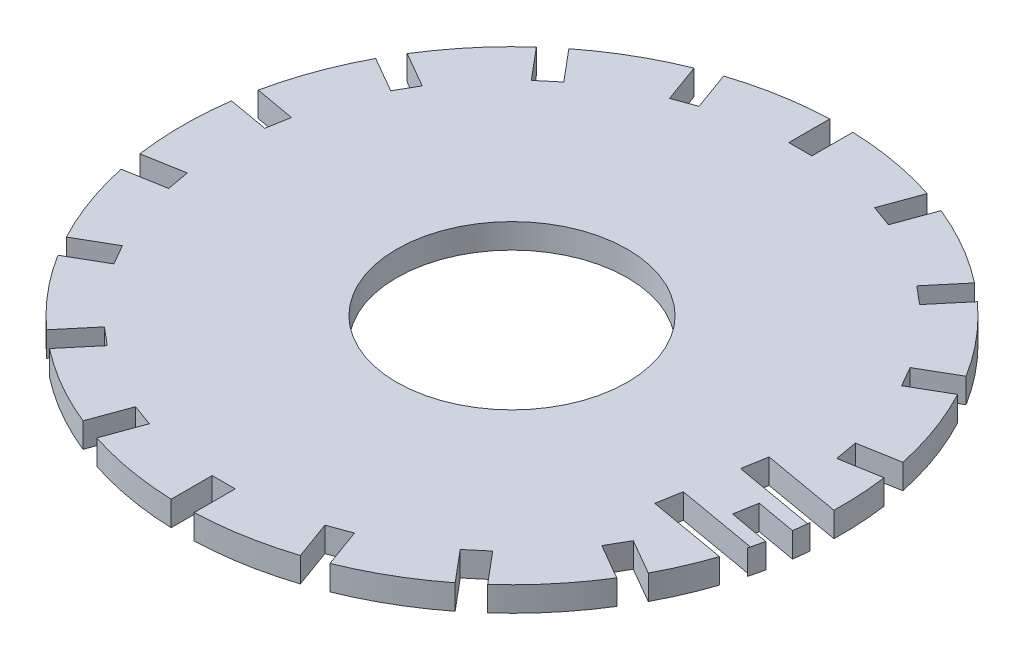
SolidWorks part; units mm, degrees
ref_plane "Plan de face" through (0, 0, 0) normal (0, 0, 1) x (1, 0, 0)
ref_plane "Plan de dessus" through (0, 0, 0) normal (0, 1, 0) x (1, 0, 0)
ref_plane "Plan de droite" through (0, 0, 0) normal (1, 0, 0) x (0, 0, -1)
sketch "Esquisse1" plane through (0, 0, 0) normal (0, 1, 0) x (1, 0, 0)
  line L0 (0, 0) -> (0, 40) construction
  line L1 (0, 40) -> (8.5644, 40) construction
  circle A0 centre (0, 0) radius 40
  circle A1 centre (0, 0) radius 14
  dimension "D1" = 80
  dimension "D2" = 28
extrude "Boss.-Extru.1" add sketch "Esquisse1" along normal blind 3
sketch "Esquisse2" plane through (0, 3, 0) normal (0, 1, 0) x (1, 0, 0)
  line L0 (0, 0) -> (0, 40) construction
  line L1 (0, 40) -> (2.8, 40) construction
  line L2 (14.9964, 37.1089) -> (13.2863, 32.4104)
  line L3 (1.4, 40) -> (-1.4, 40)
  line L4 (1.4, 40) -> (1.4, 35)
  line L5 (1.4, 35) -> (-1.4, 35)
  line L6 (-1.4, 40) -> (-1.4, 35)
  line L7 (14.9964, 37.1089) -> (12.3652, 38.0665)
  line L8 (12.3652, 38.0665) -> (10.6551, 33.3681)
  line L9 (13.2863, 32.4104) -> (10.6551, 33.3681)
  line L10 (26.784, 29.7419) -> (23.57, 25.9117)
  line L11 (26.784, 29.7419) -> (24.639, 31.5417)
  line L12 (24.639, 31.5417) -> (21.4251, 27.7115)
  line L13 (23.57, 25.9117) -> (21.4251, 27.7115)
  line L14 (35.341, 18.7876) -> (31.0109, 16.2876)
  line L15 (35.341, 18.7876) -> (33.941, 21.2124)
  line L16 (33.941, 21.2124) -> (29.6109, 18.7124)
  line L17 (31.0109, 16.2876) -> (29.6109, 18.7124)
  line L18 (39.6354, 5.5672) -> (34.7114, 4.699)
  line L19 (39.6354, 5.5672) -> (39.1492, 8.3247)
  line L20 (39.1492, 8.3247) -> (34.2252, 7.4564)
  line L21 (34.7114, 4.699) -> (34.2252, 7.4564)
  line L22 (39.1492, -8.3247) -> (34.2252, -7.4564)
  line L23 (39.1492, -8.3247) -> (39.6354, -5.5672)
  line L24 (39.6354, -5.5672) -> (34.7114, -4.699)
  line L25 (34.2252, -7.4564) -> (34.7114, -4.699)
  line L26 (33.941, -21.2124) -> (29.6109, -18.7124)
  line L27 (33.941, -21.2124) -> (35.341, -18.7876)
  line L28 (35.341, -18.7876) -> (31.0109, -16.2876)
  line L29 (29.6109, -18.7124) -> (31.0109, -16.2876)
  line L30 (24.639, -31.5417) -> (21.4251, -27.7115)
  line L31 (24.639, -31.5417) -> (26.784, -29.7419)
  line L32 (26.784, -29.7419) -> (23.57, -25.9117)
  line L33 (21.4251, -27.7115) -> (23.57, -25.9117)
  line L34 (12.3652, -38.0665) -> (10.6551, -33.3681)
  line L35 (12.3652, -38.0665) -> (14.9964, -37.1089)
  line L36 (14.9964, -37.1089) -> (13.2863, -32.4104)
  line L37 (10.6551, -33.3681) -> (13.2863, -32.4104)
  line L38 (-1.4, -40) -> (-1.4, -35)
  line L39 (-1.4, -40) -> (1.4, -40)
  line L40 (1.4, -40) -> (1.4, -35)
  line L41 (-1.4, -35) -> (1.4, -35)
  line L42 (-14.9964, -37.1089) -> (-13.2863, -32.4104)
  line L43 (-14.9964, -37.1089) -> (-12.3652, -38.0665)
  line L44 (-12.3652, -38.0665) -> (-10.6551, -33.3681)
  line L45 (-13.2863, -32.4104) -> (-10.6551, -33.3681)
  line L46 (-26.784, -29.7419) -> (-23.57, -25.9117)
  line L47 (-26.784, -29.7419) -> (-24.639, -31.5417)
  line L48 (-24.639, -31.5417) -> (-21.4251, -27.7115)
  line L49 (-23.57, -25.9117) -> (-21.4251, -27.7115)
  line L50 (-35.341, -18.7876) -> (-31.0109, -16.2876)
  line L51 (-35.341, -18.7876) -> (-33.941, -21.2124)
  line L52 (-33.941, -21.2124) -> (-29.6109, -18.7124)
  line L53 (-31.0109, -16.2876) -> (-29.6109, -18.7124)
  line L54 (-39.6354, -5.5672) -> (-34.7114, -4.699)
  line L55 (-39.6354, -5.5672) -> (-39.1492, -8.3247)
  line L56 (-39.1492, -8.3247) -> (-34.2252, -7.4564)
  line L57 (-34.7114, -4.699) -> (-34.2252, -7.4564)
  line L58 (-39.1492, 8.3247) -> (-34.2252, 7.4564)
  line L59 (-39.1492, 8.3247) -> (-39.6354, 5.5672)
  line L60 (-39.6354, 5.5672) -> (-34.7114, 4.699)
  line L61 (-34.2252, 7.4564) -> (-34.7114, 4.699)
  line L62 (-33.941, 21.2124) -> (-29.6109, 18.7124)
  line L63 (-33.941, 21.2124) -> (-35.341, 18.7876)
  line L64 (-35.341, 18.7876) -> (-31.0109, 16.2876)
  line L65 (-29.6109, 18.7124) -> (-31.0109, 16.2876)
  line L66 (-24.639, 31.5417) -> (-21.4251, 27.7115)
  line L67 (-24.639, 31.5417) -> (-26.784, 29.7419)
  line L68 (-26.784, 29.7419) -> (-23.57, 25.9117)
  line L69 (-21.4251, 27.7115) -> (-23.57, 25.9117)
  line L70 (-12.3652, 38.0665) -> (-10.6551, 33.3681)
  line L71 (-12.3652, 38.0665) -> (-14.9964, 37.1089)
  line L72 (-14.9964, 37.1089) -> (-13.2863, 32.4104)
  line L73 (-10.6551, 33.3681) -> (-13.2863, 32.4104)
  circle A0 centre (0, 0) radius 40 construction
  point P81 (0, 0)
  dimension "D1" = 2.8
  dimension "D2" = 1.4
  dimension "D3" = 5
  dimension "D4" = 18
extrude "Enlèv. mat.-Extru.1" cut sketch "Esquisse2" against normal up to next
sketch "Esquisse3" plane through (0, 3, 0) normal (0, 1, 0) x (1, 0, 0)
  line L0 (0, 0) -> (78.8444, -13.8009) construction
  line L1 (78.5839, -15.2781) -> (79.1049, -12.3236) construction
  line L10 (30.7503, 2.4571) -> (27.6781, -15.0939) construction
  line L19 (30.4533, 0.7607) -> (29.9361, -2.1944)
  line L24 (30.4533, 0.7607) -> (40.3036, -0.9635)
  line L25 (29.9361, -2.1944) -> (39.7863, -3.9185)
  line L26 (40.3036, -0.9635) -> (39.7863, -3.9185)
  line L27 (28.3843, -11.0596) -> (28.9016, -8.1045)
  line L28 (28.3843, -11.0596) -> (38.2346, -12.7838)
  line L29 (28.9016, -8.1045) -> (38.7518, -9.8287)
  line L30 (38.2346, -12.7838) -> (38.7518, -9.8287)
  dimension "D1" = 3
  dimension "D2" = 10
  dimension "D3" = 6
  dimension "D4" = 3
extrude "Enlèv. mat.-Extru.2" cut sketch "Esquisse3" against normal blind 10
